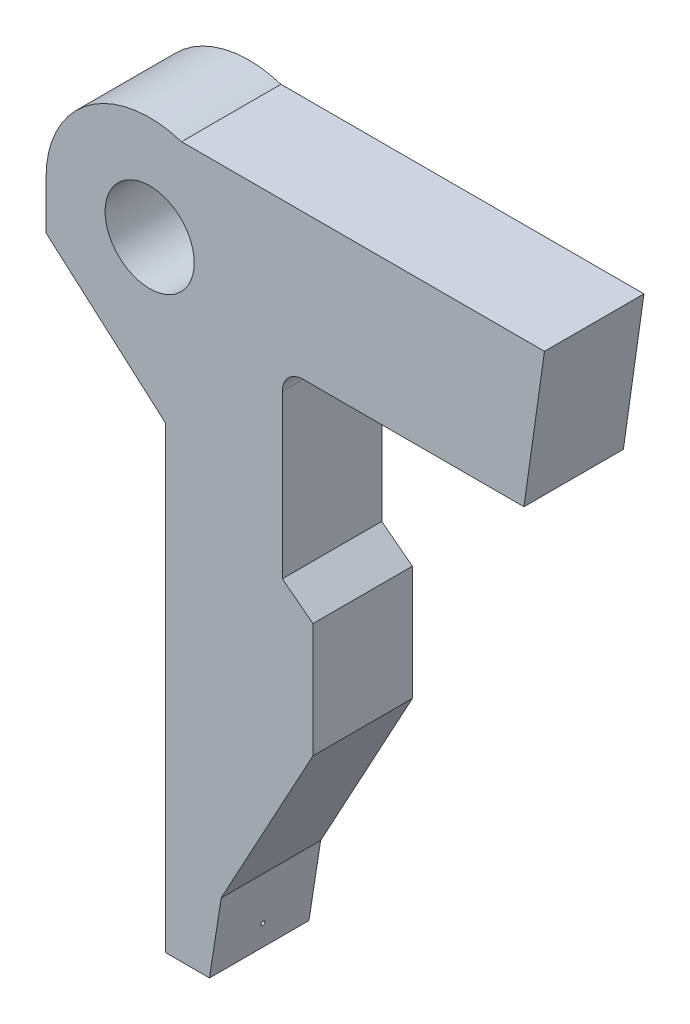
SolidWorks part; units mm, degrees
ref_plane "정면" through (0, 0, 0) normal (0, 0, 1) x (1, 0, 0)
ref_plane "윗면" through (0, 0, 0) normal (0, 1, 0) x (1, 0, 0)
ref_plane "우측면" through (0, 0, 0) normal (1, 0, 0) x (0, 0, -1)
sketch "스케치1" plane through (0, 0, 0) normal (0, 0, 1) x (1, 0, 0)
  line L0 (-5, 0) -> (-5, -2.3265)
  line L1 (0.7542, -29.5199) -> (2.8891, -29.5199)
  line L2 (6.4021, -11.0793) -> (6.4021, -3.2376)
  line L3 (7.4021, -2.2376) -> (18.0636, -2.2376)
  line L4 (18.0636, -2.2376) -> (19.056, 4.758)
  line L5 (2.8891, -29.5199) -> (3.4526, -25.8908)
  line L6 (-5, -2.3265) -> (0.7542, -7.3778)
  line L7 (0.7542, -7.3778) -> (0.7542, -29.5199)
  line L8 (19.056, 4.758) -> (1.5367, 4.758)
  line L9 (3.4526, -25.8908) -> (7.8804, -17.7409)
  line L10 (7.8804, -17.7409) -> (7.8804, -12.2111)
  line L11 (7.8804, -12.2111) -> (6.4021, -11.0793)
  circle A0 centre (0, 0) radius 2.15
  circle A1 centre (0, 0) radius 5
  arc A3 (6.4021, -3.2376) -> (7.4021, -2.2376) centre (7.4021, -3.2376) cw
  dimension "D1" = 4.3
  dimension "D2" = 10
  dimension "D3" = 1
extrude "보스-돌출1" add sketch "스케치1" along normal blind 4.8
sketch "스케치3" plane through (0.7542, 0, 0) normal (-1, 0, 0) x (0, 0, 1)
  line L0 (4.8, -29.5199) -> (0, -29.5199) construction
  circle A0 centre (2.4, -27.0199) radius 1.825
  point P2 (2.4, -29.5199)
  dimension "D2" = 3.65
  dimension "D1" = 2.5
extrude "컷-돌출1" cut sketch "스케치3" against normal blind 1.8
sketch "스케치4" plane through (2.5542, 0, 0) normal (-1, 0, 0) x (0, 0, 1)
  line L0 (2.4, -25.1949) -> (2.4, -28.8449) construction
  circle A0 centre (2.4, -27.0199) radius 1.825 construction
  circle A1 centre (2.4, -27.0199) radius 1.825 construction
  circle A2 centre (2.4, -28.3449) radius 0.1
  dimension "D1" = 0.5
extrude "컷-돌출2" cut sketch "스케치4" against normal up to next contours A2
